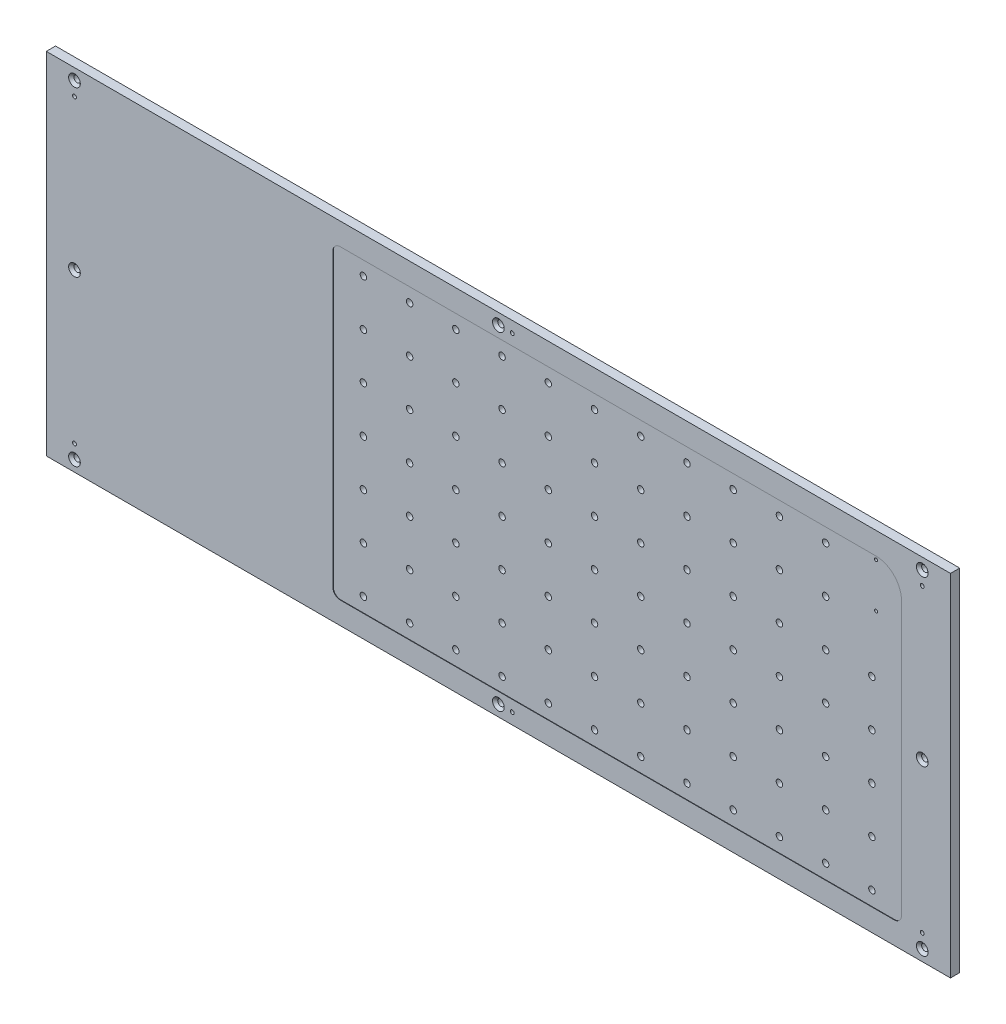
SolidWorks part; units mm, degrees
material "6061 Alloy"
ref_plane "Front Plane" through (0, 0, 0) normal (0, 0, 1) x (1, 0, 0)
ref_plane "Top Plane" through (0, 0, 0) normal (0, 1, 0) x (1, 0, 0)
ref_plane "Right Plane" through (0, 0, 0) normal (1, 0, 0) x (0, 0, -1)
sketch "Sketch1" plane through (0, 0, 0) normal (0, 0, 1) x (1, 0, 0)
  line L0 (495, -623) -> (-495, -623) construction
  line L1 (495, -60) -> (-495, -60) construction
  line L2 (495, -623) -> (-495, -623) construction
  line L3 (495, -60) -> (-495, -60) construction
  line L4 (-489, -680) -> (-489, 0) construction
  line L5 (-489, -492) -> (489, -492) construction
  line L6 (-489, -492) -> (-489, -177)
  line L7 (-489, -177) -> (489, -177) construction
  line L8 (489, -492) -> (489, -177)
  line L9 (489, -680) -> (489, 0) construction
  line L11 (-489, -524) -> (489, -524)
  line L12 (-489, -524) -> (-489, -145)
  line L13 (-489, -145) -> (489, -145)
  line L14 (489, -524) -> (489, -145)
  line L15 (489, -145) -> (428, -145)
  line L16 (489, -145) -> (489, -524)
  line L17 (489, -524) -> (428, -524)
  line L18 (428, -145) -> (428, -524) construction
  line L19 (-489, -145) -> (-171, -145)
  line L20 (-489, -145) -> (-489, -524)
  line L21 (-489, -524) -> (-171, -524)
  line L22 (-171, -145) -> (-171, -524) construction
  line M19 (-489, 0) -> (-489, -680)
  line M21 (-421, -680) -> (-421, 0)
  dimension "D1" = 117
  dimension "D2" = 432
  dimension "D3" = 32
  dimension "D4" = 32
  dimension "D5" = 61
  dimension "D7" = 978
  dimension "D8" = 318
  dimension "D6" = 379
extrude "Boss-Extrude1" add sketch "Sketch1" along normal blind 10 contours L11 L14 L8 L13 M21 | L13 L11 M19 M21
sketch "Sketch2" plane through (0, 0, 10) normal (0, 0, 1) x (1, 0, 0)
  line L0 (-489, -524) -> (489, -524) construction
  line L1 (489, -145) -> (428, -145)
  line L2 (489, -145) -> (489, -524)
  line L3 (489, -524) -> (428, -524)
  line L4 (428, -145) -> (428, -524) construction
  line L5 (458.5, -145) -> (458.5, -524) construction
  line L6 (0, -145) -> (0, -524) construction
  line L7 (-489, -145) -> (489, -145) construction
  line L8 (428, -334.5) -> (489, -334.5) construction
  line L9 (0, -145) -> (458.5, -145) construction
  line L10 (229.25, -145) -> (229.25, -524) construction
  line L11 (-489, -524) -> (489, -524) construction
  point P15 (458.5, -334.5)
  point P16 (458.5, -157)
  point P17 (458.5, -512)
  point P19 (0, -334.5)
  point P20 (0, -157)
  point P21 (0, -512)
  point P22 (-458.5, -512)
  point P23 (-458.5, -334.5)
  point P24 (-458.5, -157)
  point P30 (0, -512)
  point P31 (0, -157)
  dimension "D1" = 61
  dimension "D2" = 12
hole_wizard "CSK for M6 Flat Head Machine Screw1" positions "3DSketch1" profile "Sketch4" countersink size "M6" standard "ANSI Metric" end condition through all
sketch3d "3DSketch1"
  point P0 (458.5, -157, 10)
  point P3 (458.5, -334.5, 10)
  point P6 (458.5, -512, 10)
  point P9 (-458.5, -157, 10)
  point P12 (-458.5, -334.5, 10)
  point P15 (-458.5, -512, 10)
  point P18 (0, -157, 10)
  point P21 (0, -512, 10)
sketch "Sketch4" plane through (458.5, -157, 10) normal (1, 0, 0) x (0, -1, 0)
  line L0 (0, 0) -> (0, 10)
  line L1 (0, 10) -> (3.5, 10)
  line L2 (3.5, 10) -> (3.5, 2.8)
  line L3 (3.5, 2.8) -> (6.3, 0)
  line L5 (6.3, 0) -> (0, 0)
  line L6 (-3.5, 2.8) -> (-6.3, 0) construction
  line L11 (0, -6.35) -> (0, 107.95) construction
  dimension "Thru Hole Dia." = 7
  dimension "Thru Hole Depth" = 10
  dimension "Near C'Sink Dia." = 12.6
  dimension "Near C'Sink Angle" = 90
sketch "Sketch7" plane through (0, 0, 10) normal (0, 0, 1) x (1, 0, 0)
  line L8 (428, -145) -> (428, -524) construction
  line L9 (-489, -177) -> (489, -177) construction
  line L10 (-171, -145) -> (-171, -524) construction
  line L11 (-489, -492) -> (489, -492) construction
  line L12 (428, -145) -> (428, -524) construction
  line L13 (-489, -177) -> (489, -177) construction
  line L14 (-171, -145) -> (-171, -524) construction
  line L15 (-489, -492) -> (489, -492) construction
  line L16 (-179, -177) -> (-179, -492)
  line L17 (-171, -500) -> (428, -500)
  line L18 (-171, -169) -> (408, -169)
  line L19 (436, -197) -> (436, -492)
  line L20 (-489, -169) -> (489, -169) construction
  line L21 (436, -145) -> (436, -524) construction
  line L22 (-489, -500) -> (489, -500) construction
  line L23 (-179, -145) -> (-179, -524) construction
  arc A4 (408, -169) -> (436, -197) centre (408, -197) cw
  arc A5 (428, -500) -> (436, -492) centre (428, -492) ccw
  arc A6 (-179, -177) -> (-171, -169) centre (-171, -177) cw
  arc A7 (-179, -492) -> (-171, -500) centre (-171, -492) ccw
  dimension "D1" = 8
  dimension "D2" = 8
  dimension "D3" = 28
  dimension "D4" = 8
  dimension "D5" = 8
  dimension "D6" = 8
  dimension "D7" = 315
  dimension "D8" = 599
extrude "Cut-Extrude1" cut sketch "Sketch7" against normal blind 0.5
sketch "Sketch8" plane through (0, 0, 9.5) normal (0, 0, 1) x (1, 0, 0)
  line L0 (408, -169.5) -> (408, -224.5) construction
  line L4 (-489, -524) -> (489, -524)
  line L5 (489, -524) -> (489, -145)
  line L6 (489, -145) -> (-489, -145)
  line L7 (-489, -145) -> (-489, -524)
  line L8 (-489, -524) -> (489, -524)
  line L9 (489, -524) -> (489, -145)
  line L10 (489, -145) -> (-489, -145)
  line L11 (-489, -145) -> (-489, -524)
  arc A1 (436, -197) -> (408, -169) centre (408, -197) ccw construction
  circle A2 centre (408, -197) radius 27.5 construction
  point P10 (408, -173)
  point P11 (408, -221)
  dimension "D2" = 55
  dimension "D3" = 24
  dimension "D4" = 24
  dimension "D1" = 0
hole_wizard "M4x0.7 Tapped Hole1" positions "3DSketch3" profile "Sketch9" tap size "M4x0.7" standard "ANSI Metric" end condition through all
sketch3d "3DSketch3"
  point P0 (408, -173, 9.5)
  point P3 (408, -221, 9.5)
sketch "Sketch9" plane through (408, -173, 9.5) normal (1, 0, 0) x (0, -1, 0)
  line L0 (0, 0) -> (0, 9.5)
  line L1 (0, 9.5) -> (1.65, 9.5)
  line L2 (1.65, 9.5) -> (1.65, 0)
  line L5 (1.65, 0) -> (0, 0)
  line L11 (0, -6.35) -> (0, 107.95) construction
  dimension "Thru Tap Drill Dia." = 3.3
  dimension "Thru Tap Drill Depth" = 9.5
cosmetic thread "Hole Thread29" parameters "D2"=4
cosmetic thread "Hole Thread30" parameters "D2"=4
sketch "Sketch10" plane through (0, 0, 9.5) normal (0, 0, 1) x (1, 0, 0)
  line L1 (-146.5, -184.5) -> (-146.5, -484.5)
  line L2 (-489, -492) -> (489, -492) construction
  line L3 (-489, -177) -> (489, -177) construction
  line L5 (-171, -145) -> (-171, -524) construction
  line L6 (-146.5, -184.5) -> (403.5, -184.5)
  line L7 (428, -145) -> (428, -524) construction
  line L9 (380.5, -224.5) -> (435.5, -224.5)
  line L10 (380.5, -224.5) -> (380.5, -169.5)
  line L11 (380.5, -169.5) -> (435.5, -169.5)
  line L12 (435.5, -224.5) -> (435.5, -169.5)
  circle A0 centre (408, -197) radius 27.5
  arc A1 (436, -197) -> (408, -169) centre (408, -197) ccw construction
  dimension "D7" = 55
  dimension "D1" = 7.5
  dimension "D2" = 7.5
  dimension "D3" = 300
  dimension "D4" = 24.5
  dimension "D5" = 24.5
  dimension "D6" = 550
hole_wizard "M8x1.0 Tapped Hole1" positions "3DSketch4" profile "Sketch11" tap size "M8x1.0" standard "ANSI Metric" end condition through all
sketch3d "3DSketch4"
  point P0 (-146.5, -184.5, 9.5)
sketch "Sketch11" plane through (-146.5, -184.5, 9.5) normal (1, 0, 0) x (0, -1, 0)
  line L0 (0, 0) -> (0, 9.5)
  line L1 (0, 9.5) -> (3.5, 9.5)
  line L2 (3.5, 9.5) -> (3.5, 0)
  line L5 (3.5, 0) -> (0, 0)
  line L11 (0, -6.35) -> (0, 107.95) construction
  dimension "Thru Tap Drill Dia." = 7
  dimension "Thru Tap Drill Depth" = 9.5
cosmetic thread "Hole Thread5" parameters "D2"=8
pattern_linear "LPattern1" count 11 spacing 50 along (1, 0, 0) count 2 spacing 50 along (0, -1, 0) of "M8x1.0 Tapped Hole1"
cosmetic thread "Hole Thread6" parameters "D2"=8
cosmetic thread "Hole Thread7" parameters "D2"=8
cosmetic thread "Hole Thread8" parameters "D2"=8
cosmetic thread "Hole Thread9" parameters "D2"=8
cosmetic thread "Hole Thread10" parameters "D2"=8
cosmetic thread "Hole Thread11" parameters "D2"=8
cosmetic thread "Hole Thread12" parameters "D2"=8
cosmetic thread "Hole Thread13" parameters "D2"=8
cosmetic thread "Hole Thread14" parameters "D2"=8
cosmetic thread "Hole Thread15" parameters "D2"=8
cosmetic thread "Hole Thread16" parameters "D2"=8
cosmetic thread "Hole Thread17" parameters "D2"=8
cosmetic thread "Hole Thread18" parameters "D2"=8
cosmetic thread "Hole Thread19" parameters "D2"=8
cosmetic thread "Hole Thread20" parameters "D2"=8
cosmetic thread "Hole Thread21" parameters "D2"=8
cosmetic thread "Hole Thread22" parameters "D2"=8
cosmetic thread "Hole Thread23" parameters "D2"=8
cosmetic thread "Hole Thread24" parameters "D2"=8
cosmetic thread "Hole Thread25" parameters "D2"=8
cosmetic thread "Hole Thread26" parameters "D2"=8
hole_wizard "M8x1.0 Tapped Hole2" positions "3DSketch5" profile "Sketch12" tap size "M8x1.0" standard "ANSI Metric" end condition through all
sketch3d "3DSketch5"
  point P0 (-146.5, -484.5, 9.5)
sketch "Sketch12" plane through (-146.5, -484.5, 9.5) normal (1, 0, 0) x (0, -1, 0)
  line L0 (0, 0) -> (0, 9.5)
  line L1 (0, 9.5) -> (3.5, 9.5)
  line L2 (3.5, 9.5) -> (3.5, 0)
  line L5 (3.5, 0) -> (0, 0)
  line L11 (0, -6.35) -> (0, 107.95) construction
  dimension "Thru Tap Drill Dia." = 7
  dimension "Thru Tap Drill Depth" = 9.5
cosmetic thread "Hole Thread31" parameters "D2"=8
pattern_linear "LPattern2" count 12 spacing 50 along (1, 0, 0) count 5 spacing 50 along (0, 1, 0) of "M8x1.0 Tapped Hole2"
cosmetic thread "Hole Thread32" parameters "D2"=8
cosmetic thread "Hole Thread33" parameters "D2"=8
cosmetic thread "Hole Thread34" parameters "D2"=8
cosmetic thread "Hole Thread35" parameters "D2"=8
cosmetic thread "Hole Thread36" parameters "D2"=8
cosmetic thread "Hole Thread37" parameters "D2"=8
cosmetic thread "Hole Thread38" parameters "D2"=8
cosmetic thread "Hole Thread39" parameters "D2"=8
cosmetic thread "Hole Thread40" parameters "D2"=8
cosmetic thread "Hole Thread41" parameters "D2"=8
cosmetic thread "Hole Thread42" parameters "D2"=8
cosmetic thread "Hole Thread43" parameters "D2"=8
cosmetic thread "Hole Thread44" parameters "D2"=8
cosmetic thread "Hole Thread45" parameters "D2"=8
cosmetic thread "Hole Thread46" parameters "D2"=8
cosmetic thread "Hole Thread47" parameters "D2"=8
cosmetic thread "Hole Thread48" parameters "D2"=8
cosmetic thread "Hole Thread49" parameters "D2"=8
cosmetic thread "Hole Thread50" parameters "D2"=8
cosmetic thread "Hole Thread51" parameters "D2"=8
cosmetic thread "Hole Thread52" parameters "D2"=8
cosmetic thread "Hole Thread53" parameters "D2"=8
cosmetic thread "Hole Thread54" parameters "D2"=8
cosmetic thread "Hole Thread55" parameters "D2"=8
cosmetic thread "Hole Thread56" parameters "D2"=8
cosmetic thread "Hole Thread57" parameters "D2"=8
cosmetic thread "Hole Thread58" parameters "D2"=8
cosmetic thread "Hole Thread59" parameters "D2"=8
cosmetic thread "Hole Thread60" parameters "D2"=8
cosmetic thread "Hole Thread61" parameters "D2"=8
cosmetic thread "Hole Thread62" parameters "D2"=8
cosmetic thread "Hole Thread63" parameters "D2"=8
cosmetic thread "Hole Thread64" parameters "D2"=8
cosmetic thread "Hole Thread65" parameters "D2"=8
cosmetic thread "Hole Thread66" parameters "D2"=8
cosmetic thread "Hole Thread67" parameters "D2"=8
cosmetic thread "Hole Thread68" parameters "D2"=8
cosmetic thread "Hole Thread69" parameters "D2"=8
cosmetic thread "Hole Thread70" parameters "D2"=8
cosmetic thread "Hole Thread71" parameters "D2"=8
cosmetic thread "Hole Thread72" parameters "D2"=8
cosmetic thread "Hole Thread73" parameters "D2"=8
cosmetic thread "Hole Thread74" parameters "D2"=8
cosmetic thread "Hole Thread75" parameters "D2"=8
cosmetic thread "Hole Thread76" parameters "D2"=8
cosmetic thread "Hole Thread77" parameters "D2"=8
cosmetic thread "Hole Thread78" parameters "D2"=8
cosmetic thread "Hole Thread79" parameters "D2"=8
cosmetic thread "Hole Thread80" parameters "D2"=8
cosmetic thread "Hole Thread81" parameters "D2"=8
cosmetic thread "Hole Thread82" parameters "D2"=8
cosmetic thread "Hole Thread83" parameters "D2"=8
cosmetic thread "Hole Thread84" parameters "D2"=8
cosmetic thread "Hole Thread85" parameters "D2"=8
cosmetic thread "Hole Thread86" parameters "D2"=8
cosmetic thread "Hole Thread87" parameters "D2"=8
cosmetic thread "Hole Thread88" parameters "D2"=8
cosmetic thread "Hole Thread89" parameters "D2"=8
cosmetic thread "Hole Thread90" parameters "D2"=8
sketch "Sketch13" plane through (0, 0, 9.5) normal (0, 0, 1) x (1, 0, 0)
  circle A0 centre (3.5, -334.5) radius 3.5 construction
  circle A1 centre (3.5, -334.5) radius 3.5
sketch "Sketch14" plane through (0, 0, 10) normal (0, 0, 1) x (1, 0, 0)
  line L0 (458.5, -157) -> (458.5, -512) construction
  line L1 (-458.5, -497) -> (458.5, -497) construction
  line L2 (-458.5, -497) -> (-458.5, -172) construction
  line L3 (-458.5, -172) -> (458.5, -172) construction
  line L4 (458.5, -497) -> (458.5, -172) construction
  line L5 (-458.5, -512) -> (-458.5, -157) construction
  line L7 (0, -157) -> (15, -157) construction
  line L8 (0, -157) -> (0, -512) construction
  line L9 (0, -512) -> (15, -512) construction
  line L10 (15, -157) -> (15, -512) construction
  circle A0 centre (0, -512) radius 6.3 construction
  dimension "D1" = 15
  dimension "D2" = 15
  dimension "D3" = 15
hole_wizard "M5x0.8 Tapped Hole1" positions "3DSketch6" profile "Sketch16" tap size "M5x0.8" standard "ANSI Metric" end condition through all
sketch3d "3DSketch6"
  point P0 (-458.5, -497, 10)
  point P3 (-458.5, -172, 10)
  point P6 (458.5, -172, 10)
  point P9 (458.5, -497, 10)
  point P13 (15, -157, 10)
  point P16 (15, -512, 10)
sketch "Sketch16" plane through (-458.5, -497, 10) normal (1, 0, 0) x (0, -1, 0)
  line L0 (0, 0) -> (0, 10)
  line L1 (0, 10) -> (2.1, 10)
  line L2 (2.1, 10) -> (2.1, 0)
  line L5 (2.1, 0) -> (0, 0)
  line L11 (0, -6.35) -> (0, 107.95) construction
  dimension "Thru Tap Drill Dia." = 4.2
  dimension "Thru Tap Drill Depth" = 10
cosmetic thread "Hole Thread1" parameters "D2"=5
cosmetic thread "Hole Thread2" parameters "D2"=5
cosmetic thread "Hole Thread3" parameters "D2"=5
cosmetic thread "Hole Thread4" parameters "D2"=5
cosmetic thread "Hole Thread27" parameters "D2"=5
cosmetic thread "Hole Thread28" parameters "D2"=5
equation "\"border\"= 2 * \"socket_radius\" + \"cutterDiam\" / 2"
equation "\"D3@Sketch1\"= \"border\""
equation "\"D4@Sketch1\"= \"D3@Sketch1\""
equation "\"D2@Sketch2\"= \"socket_radius\""
equation "\"front_border\"= 61"
equation "\"D1@Sketch2\"= \"D5@Sketch1\""
equation "\"D5@Sketch1\"= \"front_border\""
equation "\"socket_radius\"= 12"
equation "\"cutterDiam\"= 16"
